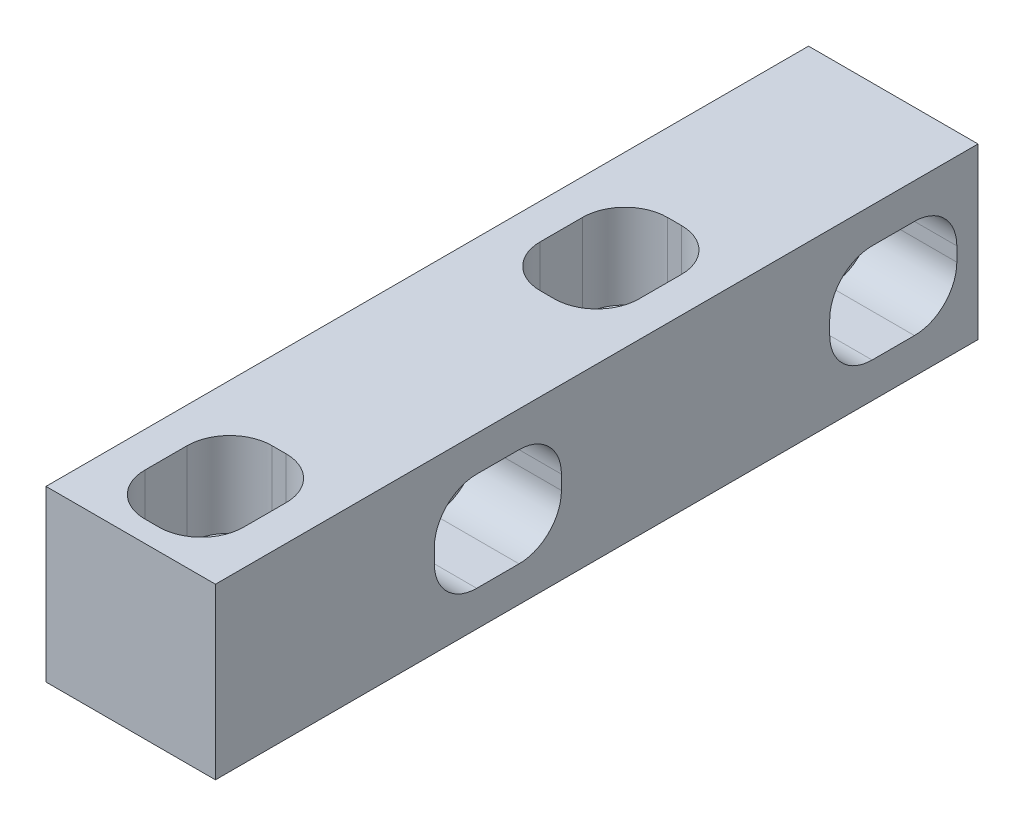
SolidWorks part; units mm, degrees
ref_plane "Front Plane" through (0, 0, 0) normal (0, 0, 1) x (1, 0, 0)
ref_plane "Top Plane" through (0, 0, 0) normal (0, 1, 0) x (1, 0, 0)
ref_plane "Right Plane" through (0, 0, 0) normal (1, 0, 0) x (0, 0, -1)
sketch "Sketch1" plane through (0, 0, 0) normal (0, 0, 1) x (1, 0, 0)
  line L1 (6, 6) -> (-6, 6)
  line L2 (6, 6) -> (6, -6)
  line L3 (6, -6) -> (-6, -6)
  line L4 (-6, 6) -> (-6, -6)
  line L5 (6, 6) -> (-6, -6) construction
  line L6 (6, -6) -> (-6, 6) construction
  point P0 (0, 0)
  dimension "D1" = 12
  dimension "D2" = 12
extrude "Boss-Extrude1" add sketch "Sketch1" along normal blind 54
sketch "Sketch2" plane through (0, 6, 0) normal (0, 1, 0) x (1, 0, 0)
  line L0 (0, 0) -> (0, -20) construction
  line L1 (6, 0) -> (-6, 0) construction
  line L2 (0, -54) -> (0, -48) construction
  line L3 (6, -54) -> (-6, -54) construction
  circle A1 centre (0, -20) radius 2
  circle A2 centre (0, -48) radius 2
  dimension "D1" = 4
  dimension "D4" = 4
  dimension "D2" = 20
  dimension "D3" = 6
extrude "Cut-Extrude1" cut sketch "Sketch2" against normal blind 14
sketch "Sketch3" plane through (-6, 0, 0) normal (-1, 0, 0) x (0, 0, 1)
  line L0 (54, 0) -> (34, 0) construction
  line L1 (54, 6) -> (54, -6) construction
  line L2 (0, 0) -> (6, 0) construction
  line L3 (0, 6) -> (0, -6) construction
  circle A0 centre (34, 0) radius 2
  circle A1 centre (6, 0) radius 2
  dimension "D2" = 4
  dimension "D4" = 4
  dimension "D1" = 20
  dimension "D3" = 6
extrude "Cut-Extrude2" cut sketch "Sketch3" against normal blind 14
sketch "Sketch4" plane through (6, 0, 0) normal (1, 0, 0) x (0, 0, -1)
  line L0 (-6, 0) -> (-34, 0) construction
  line L1 (-4.5, -3.5) -> (-7.5, -3.5)
  line L2 (-1.5, -0.5) -> (-1.5, 0.5)
  line L3 (-4.5, 3.5) -> (-7.5, 3.5)
  line L4 (-10.5, -0.5) -> (-10.5, 0.5)
  line L5 (-1.5, -3.5) -> (-10.5, 3.5) construction
  line L6 (-1.5, 3.5) -> (-10.5, -3.5) construction
  line L7 (-20, 0) -> (-20, -6) construction
  line L8 (-54, -6) -> (0, -6) construction
  line L9 (-38.5, -0.5) -> (-38.5, 0.5)
  line L10 (-35.5, 3.5) -> (-32.5, 3.5)
  line L11 (-29.5, -0.5) -> (-29.5, 0.5)
  line L12 (-35.5, -3.5) -> (-32.5, -3.5)
  arc A0 (-1.5, 0.5) -> (-4.5, 3.5) centre (-4.5, 0.5) ccw
  arc A1 (-7.5, 3.5) -> (-10.5, 0.5) centre (-7.5, 0.5) ccw
  arc A2 (-7.5, -3.5) -> (-10.5, -0.5) centre (-7.5, -0.5) cw
  arc A3 (-4.5, -3.5) -> (-1.5, -0.5) centre (-4.5, -0.5) ccw
  arc A4 (-38.5, 0.5) -> (-35.5, 3.5) centre (-35.5, 0.5) cw
  arc A5 (-32.5, 3.5) -> (-29.5, 0.5) centre (-32.5, 0.5) cw
  arc A6 (-32.5, -3.5) -> (-29.5, -0.5) centre (-32.5, -0.5) ccw
  arc A7 (-35.5, -3.5) -> (-38.5, -0.5) centre (-35.5, -0.5) cw
  point P0 (-6, 0)
  dimension "D3" = 3
  dimension "D1" = 7
  dimension "D2" = 9
extrude "Cut-Extrude3" cut sketch "Sketch4" against normal blind 6
sketch "Sketch5" plane through (0, 6, 0) normal (0, 1, 0) x (1, 0, 0)
  line L0 (0, -48) -> (0, -20) construction
  line L1 (0, -34) -> (-6, -34) construction
  line L2 (-0.5, -52.5) -> (0.5, -52.5)
  line L3 (-3.5, -49.5) -> (-3.5, -46.5)
  line L4 (-0.5, -43.5) -> (0.5, -43.5)
  line L5 (3.5, -49.5) -> (3.5, -46.5)
  line L6 (-3.5, -52.5) -> (3.5, -43.5) construction
  line L7 (-3.5, -43.5) -> (3.5, -52.5) construction
  line L8 (-6, -54) -> (-6, 0) construction
  line L9 (-0.5, -24.5) -> (0.5, -24.5)
  line L10 (3.5, -18.5) -> (3.5, -21.5)
  line L11 (-0.5, -15.5) -> (0.5, -15.5)
  line L12 (-3.5, -18.5) -> (-3.5, -21.5)
  arc A0 (0.5, -52.5) -> (3.5, -49.5) centre (0.5, -49.5) ccw
  arc A1 (0.5, -43.5) -> (3.5, -46.5) centre (0.5, -46.5) cw
  arc A2 (-3.5, -46.5) -> (-0.5, -43.5) centre (-0.5, -46.5) cw
  arc A3 (-0.5, -52.5) -> (-3.5, -49.5) centre (-0.5, -49.5) cw
  arc A4 (0.5, -24.5) -> (3.5, -21.5) centre (0.5, -21.5) ccw
  arc A5 (0.5, -15.5) -> (3.5, -18.5) centre (0.5, -18.5) cw
  arc A6 (-3.5, -21.5) -> (-0.5, -24.5) centre (-0.5, -21.5) ccw
  arc A7 (-0.5, -15.5) -> (-3.5, -18.5) centre (-0.5, -18.5) ccw
  dimension "D3" = 3
  dimension "D1" = 7
  dimension "D2" = 9
extrude "Cut-Extrude4" cut sketch "Sketch5" against normal blind 6
